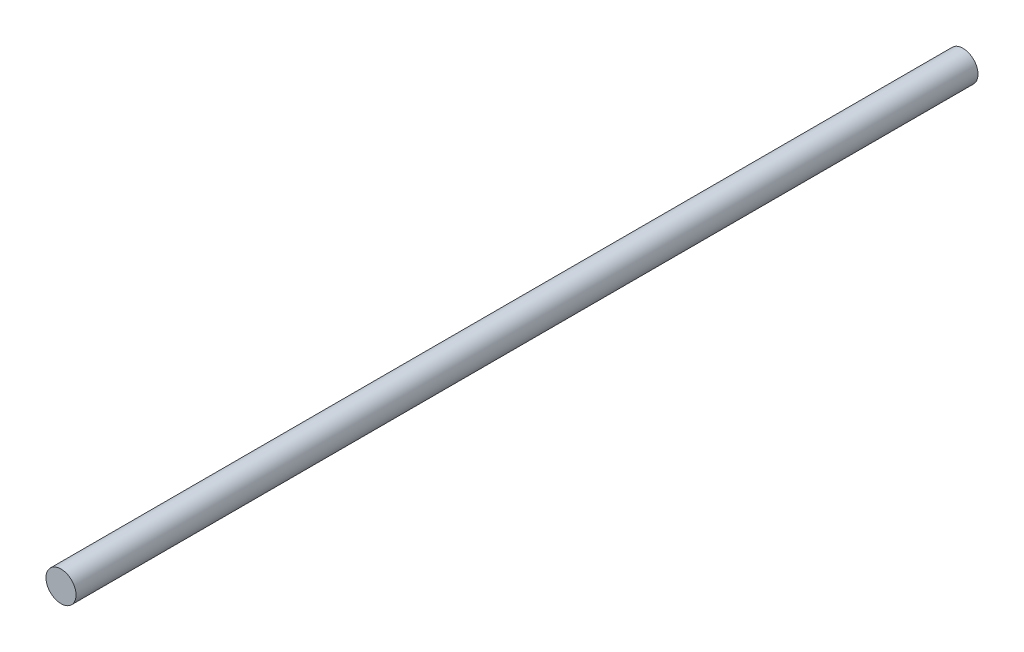
SolidWorks part; units mm, degrees
material "Stainless Steel (ferritic)"
ref_plane "Ebene vorne" through (0, 0, 0) normal (0, 0, 1) x (1, 0, 0)
ref_plane "Ebene oben" through (0, 0, 0) normal (0, 1, 0) x (1, 0, 0)
ref_plane "Ebene rechts" through (0, 0, 0) normal (1, 0, 0) x (0, 0, -1)
sketch "Sketch1" plane through (0, 0, 0) normal (0, 0, 1) x (1, 0, 0)
  circle A0 centre (0, 0) radius 2
  dimension "D1" = 4
extrude "Boss-Extrude1" add sketch "Sketch1" along normal blind 120
